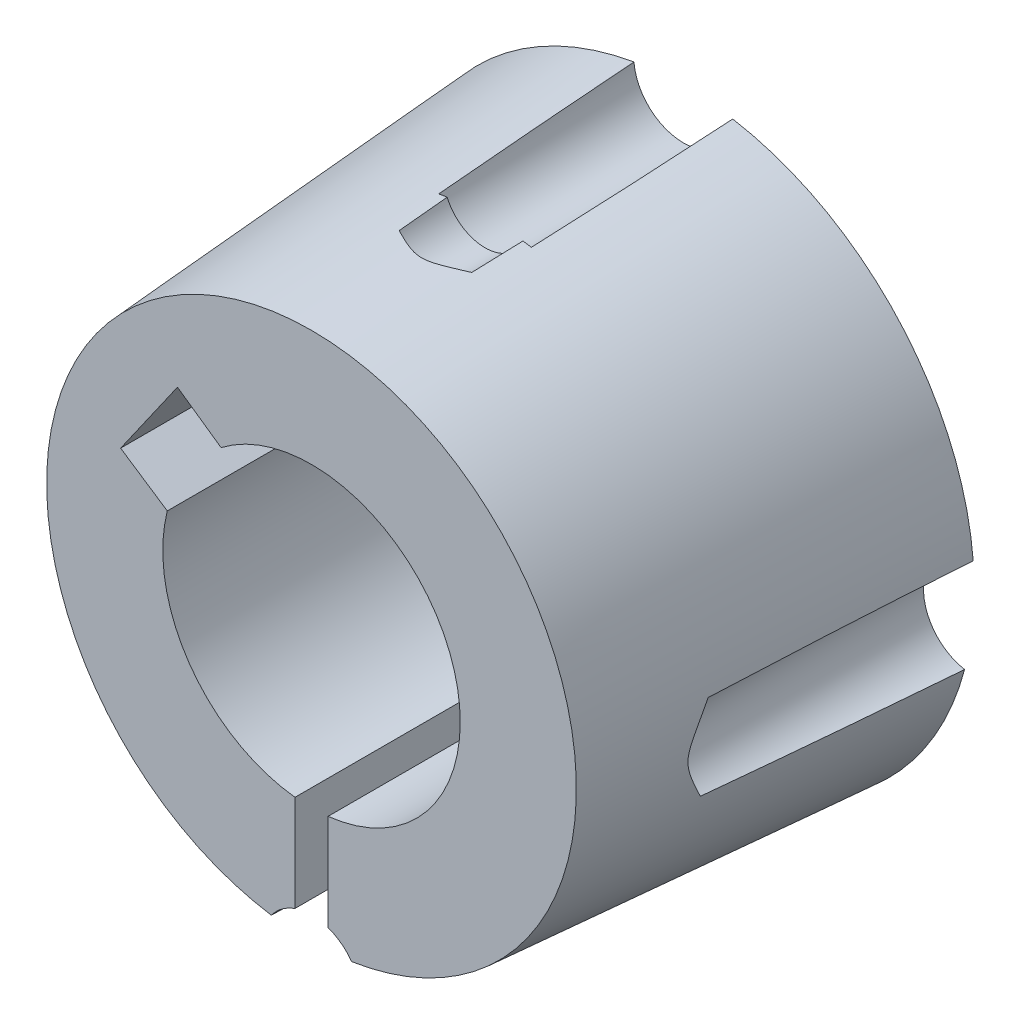
SolidWorks part; units mm, degrees
ref_plane "Front Plane" through (0, 0, 0) normal (0, 0, 1) x (1, 0, 0)
ref_plane "Top Plane" through (0, 0, 0) normal (0, 1, 0) x (1, 0, 0)
ref_plane "Right Plane" through (0, 0, 0) normal (1, 0, 0) x (0, 0, -1)
sketch "Sketch1" plane through (0, 0, 0) normal (0, 0, 1) x (1, 0, 0)
  circle A0 centre (0, 0) radius 50
extrude "Extrude1" add sketch "Sketch1" along normal blind 22.5
sketch "Sketch4" plane through (0, 0, 0) normal (0, 0, -1) x (-1, 0, 0)
  circle A0 centre (0, 0) radius 17.6
  circle M1 centre (0, 0) radius 50
  dimension "LargeEnd" = 35.2
hole_wizard "Ø6.0 (6) Diameter Hole2" positions "3DSketch2" profile "Sketch5" hole size "Ø6.0" standard "BSI"
sketch3d "3DSketch2"
  line L0 (0, 0, 0) -> (0, 42.3372, 0) construction
  line L1 (0, 42.3372, 0) -> (0, 0, 0) construction
  line L2 (0, 0, 0) -> (-17.533, -1.5339, 0) construction
  line L3 (-17.533, -1.5339, 0) -> (0, 0, 0) construction
  line L4 (0, 0, 0) -> (17.533, -1.5339, 0) construction
  circle A0 centre (0, 0, 0) radius 17.6 construction
  point P0 (17.533, -1.5339, 0)
  point P4 (0, 0, -17.6)
  point P5 (-17.533, -1.5339, 0)
  dimension "D1" = 95
  dimension "D2" = 95
sketch "Sketch5" plane through (17.533, -1.5339, 0) normal (1, 0, 0) x (0, 1, 0)
  line L0 (0, 0) -> (0, 16.8026)
  line L1 (0, 16.8026) -> (3, 15)
  line L2 (3, 15) -> (3, 0)
  line L5 (3, 0) -> (0, 0)
  line L10 (0, 16.8026) -> (-3, 15) construction
  line L11 (0, -6.35) -> (0, 107.95) construction
  dimension "HoleDia" = 6
  dimension "Hole Depth" = 15
  dimension "Drill Angle" = 118
extrude "Cut-Extrude1" cut sketch "Sketch4" against normal through all draft 4 contours A0 M1 draft outward yes
sketch "Sketch6" plane through (0, 0, 0) normal (0, 0, -1) x (-1, 0, 0)
  circle A0 centre (0, 0) radius 9
  dimension "Bore" = 18
extrude "Cut-Extrude2" cut sketch "Sketch6" against normal through all
sketch "Sketch11" plane through (0, 0, 0) normal (0, 0, -1) x (-1, 0, 0)
  line L1 (-1, -4) -> (1, -4)
  line L2 (-1, -4) -> (-1, -104)
  line L3 (-1, -104) -> (1, -104)
  line L4 (1, -4) -> (1, -104)
  dimension "D1" = 4
  dimension "D2" = 1
  dimension "D3" = 2
  dimension "D4" = 100
extrude "Cut-Extrude3" cut sketch "Sketch11" against normal through all
sketch "Sketch12" plane through (0, 0, 0) normal (0, 0, 1) x (1, 0, 0)
  line L0 (0, 0) -> (0, -54.9644) construction
  circle A0 centre (0, -17.6) radius 3
  circle A1 centre (0, 0) radius 17.6 construction
extrude "Cut-Extrude4" cut sketch "Sketch12" along normal through all
hole_wizard "M6x1.0 Tapped Hole2" positions "Sketch15" profile "Sketch14" tap size "M6x1.0" standard "BSI"
sketch "Sketch15" plane through (0, 0, 0) normal (0, 0, -1) x (-1, 0, 0)
  line L0 (0, 0) -> (0, 42.3372) construction
  circle A0 centre (0, 0) radius 17.6 construction
  point P0 (0, 17.6)
sketch "Sketch14" plane through (0, 17.6, 0) normal (1, 0, 0) x (0, 1, 0)
  line L0 (0, 0) -> (0, 16.5022)
  line L1 (0, 16.5022) -> (2.5, 15)
  line L2 (2.5, 15) -> (2.5, 12)
  line L3 (2.5, 12) -> (3, 12)
  line L4 (3, 12) -> (3, 0)
  line L5 (3, 0) -> (0, 0)
  line L10 (0, 16.5022) -> (-2.5, 15) construction
  line L11 (0, -6.35) -> (0, 107.95) construction
  dimension "TapDrillDia" = 5
  dimension "Tap Drill Depth" = 15
  dimension "ThreadMajorDia" = 6
  dimension "Thread Depth" = 12
  dimension "Drill Angle" = 118
sketch "Sketch18" plane through (0, 0, 0) normal (0, 0, -1) x (-1, 0, 0)
  line L1 (8.1108, 8.9909) -> (11.5506, 4.0747)
  line L2 (8.1108, 8.9909) -> (-0.7368, 2.7957)
  line L3 (-0.7368, 2.7957) -> (2.5543, -1.9045)
  line L4 (11.5506, 4.0747) -> (2.5543, -1.9045)
  dimension "KeyWidth" = 6
  dimension "KeyDepth" = 11.8
  dimension "D1" = 1
  dimension "D2" = 3
extrude "Cut-Extrude5" cut sketch "Sketch18" against normal through all
sketch "Sketch19" plane through (0, 0, 0) normal (0, 0, -1) x (-1, 0, 0)
  line L0 (-3.9586, 13.0111) -> (-5.1229, 16.8379) construction
  line L1 (-13.2229, 3.1806) -> (-17.1119, 4.116) construction
  arc A0 (-3.9586, 13.0111) -> (-13.2229, 3.1806) centre (0, 0) ccw construction
  arc A1 (-5.1229, 16.8379) -> (-17.1119, 4.116) centre (0, 0) ccw construction
  circle A2 centre (0, 0) radius 17.6 construction
  text T0 "<b>Taper - Lock</b>" font "Century Gothic" height in points 6
  dimension "D1" = 17.6
  dimension "D2" = 13.6
extrude "Cut-Extrude6" cut sketch "Sketch19" against normal blind 0.5
equation "\"D2@Sketch18\" = 0.5 * \"KeyWidth@Sketch18\""
equation "\"D2@Sketch19\" = \"LargeEnd@Sketch4\" / 2 - 4"
